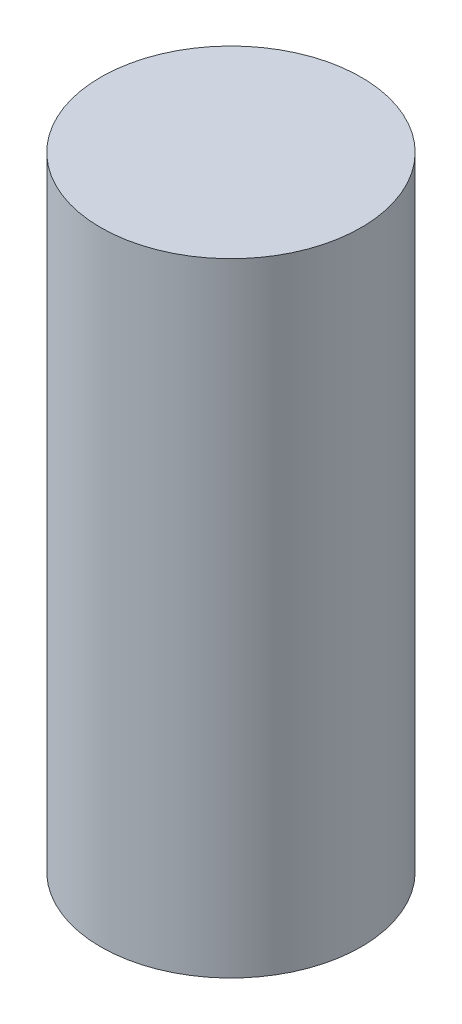
SolidWorks part; units mm, degrees
ref_plane "Front Plane" through (0, 0, 0) normal (0, 0, 1) x (1, 0, 0)
ref_plane "Top Plane" through (0, 0, 0) normal (0, 1, 0) x (1, 0, 0)
ref_plane "Right Plane" through (0, 0, 0) normal (1, 0, 0) x (0, 0, -1)
sketch "Sketch1" plane through (0, 0, 0) normal (0, 1, 0) x (1, 0, 0)
  circle A0 centre (0, 0) radius 3
  dimension "D1" = 6
extrude "Boss-Extrude1" add sketch "Sketch1" along normal blind 14.346
equation "\"bearing_21_OD\"= 21mm"
equation "\"pin_cirlce_diameter\"= 75mm"
equation "\"pin_diam\"= 6mm"
equation "\"gear_thickness\"= 4mm"
equation "\"ball_bearing_diam\"= 3.214mm"
equation "\"bearing_21_outer_clearance\"= 0.127mm'change this"
equation "\"bearing_15_OD\"= 15mm"
equation "\"bearing_15_outer_clearance\"= 0mm'change this"
equation "\"thrust_bearing_thickness\"= 5mm'measure this irl and change"
equation "\"D1@Boss-Extrude1\"=\"ballBearDiam\"*1.50+2*\"sheetThickness\""
equation "\"largeBearOD\"= 21mm"
equation "\"largeBearID\"= 15mm"
equation "\"largeBearOTight\"= 0.127mm'calibrate - hold onto gears"
equation "\"largeBearITight\"= 0mm'calibrate - hold onto eccentric nut"
equation "\"largeBearFlangeDiam\"= 22.5mm"
equation "\"largeBearFlangeWidth\"= 0.8mm"
equation "\"smallBearOD\"= 15mm"
equation "\"smallBearOTight\"= 0mm'calibrate - hold onto bottom of gearbox"
equation "\"smallBearOLoose\"= 0mm'calibrate - able to take off topHat"
equation "\"smallBearID\"= 10mm"
equation "\"smallBearITight\"= 0mm'hold onto "
equation "\"pinCircleDiam\"= 75mm"
equation "\"pinDiam\"= 6mm"
equation "\"sheetThickness\"= 0.1875in"
equation "\"ballBearDiam\"= 3.214mm"
equation "\"thrustBearingThickness\"= 5mm'measure this irl and change"
equation "\"thrustBearingID\"= 0mm'measure this irl and change"
equation "\"thrustBearingOD\"= 0mm'measure this irl and change"
equation "\"eccentricity\"= 1mm"
equation "\"D1@Sketch1\"=\"pinDiam\""
